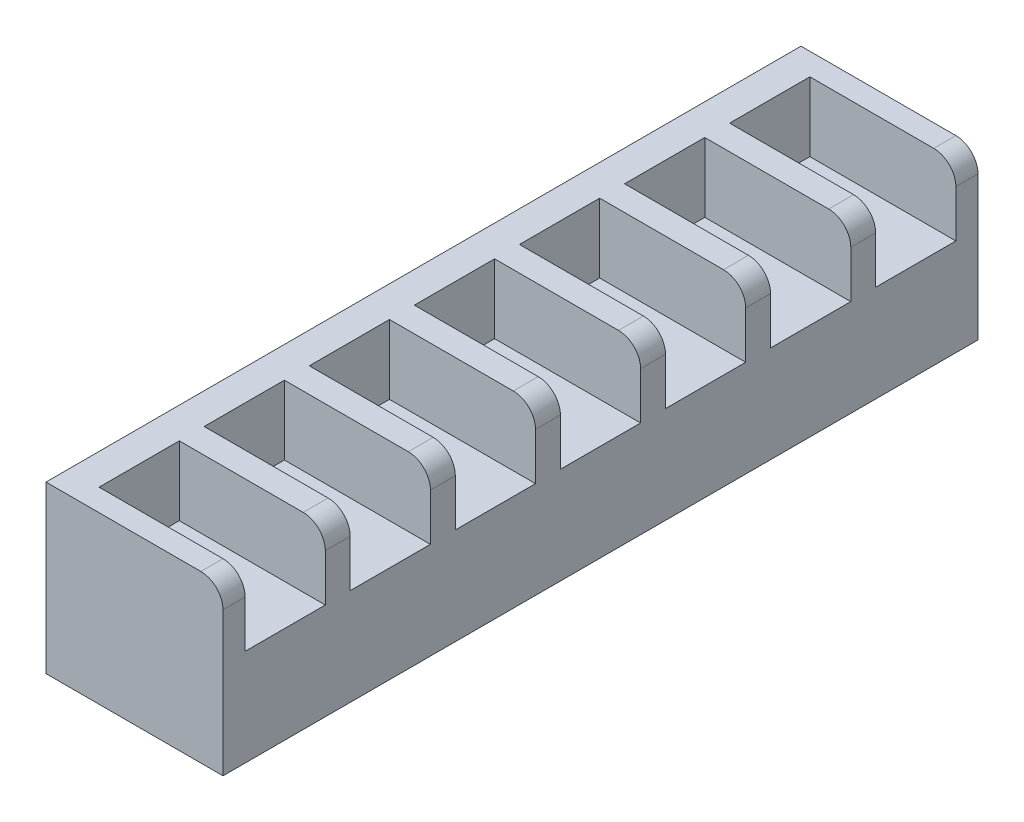
SolidWorks part; units mm, degrees
ref_plane "Front" through (0, 0, 0) normal (0, 0, 1) x (1, 0, 0)
ref_plane "Top" through (0, 0, 0) normal (0, 1, 0) x (1, 0, 0)
ref_plane "Right" through (0, 0, 0) normal (1, 0, 0) x (0, 0, -1)
sketch "Sketch1" plane through (0, 0, 0) normal (0, 1, 0) x (1, 0, 0)
  line L0 (0, 27.3586) -> (0, 0) construction
  line L1 (-8, 34.125) -> (8, 34.125)
  line L2 (-8, 34.125) -> (-8, -34.125)
  line L3 (-8, -34.125) -> (8, -34.125)
  line L4 (8, 34.125) -> (8, -34.125)
  line L5 (0, 0) -> (5.505, 0) construction
  dimension "D1" = 68.25
  dimension "D2" = 16
extrude "Boss-Extrude1" add sketch "Sketch1" along normal blind 15
fillet "Fillet1" radius 2 1 edges at (8, 15, 0)
sketch "Sketch2" plane through (0, 15, 0) normal (0, 1, 0) x (1, 0, 0)
  line L0 (-8, -34.125) -> (6, -34.125) construction
  line L1 (-5.2, -32.125) -> (8, -32.125)
  line L2 (-5.2, -32.125) -> (-5.2, -24.875)
  line L3 (-5.2, -24.875) -> (8, -24.875)
  line L4 (8, -32.125) -> (8, -24.875)
  line L5 (8, 34.125) -> (8, -34.125) construction
  dimension "D1" = 2
  dimension "D2" = 7.25
  dimension "D3" = 13.2
extrude "Cut-Extrude1" cut sketch "Sketch2" against normal blind 6.25
pattern_linear "LPattern1" count 7 spacing 9.5 along (0, 0, -1) of "Cut-Extrude1"
